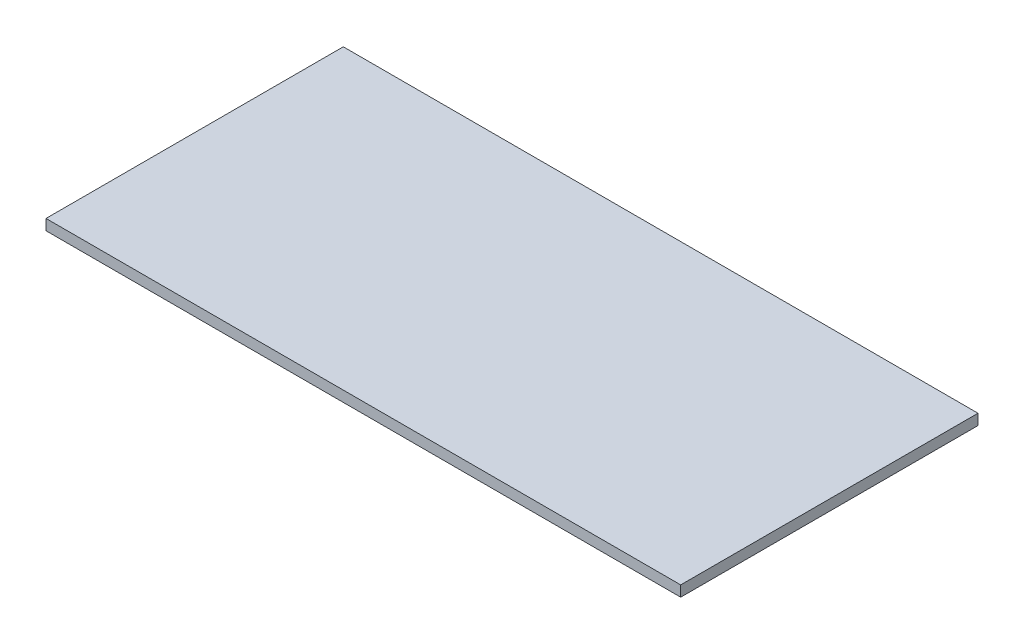
SolidWorks part; units mm, degrees
ref_plane "Front Plane" through (0, 0, 0) normal (0, 0, 1) x (1, 0, 0)
ref_plane "Top Plane" through (0, 0, 0) normal (0, 1, 0) x (1, 0, 0)
ref_plane "Right Plane" through (0, 0, 0) normal (1, 0, 0) x (0, 0, -1)
sketch "Sketch1" plane through (0, 0, 0) normal (0, 1, 0) x (1, 0, 0)
  line L1 (95, 44.5) -> (-95, 44.5)
  line L2 (95, 44.5) -> (95, -44.5)
  line L3 (95, -44.5) -> (-95, -44.5)
  line L4 (-95, 44.5) -> (-95, -44.5)
  line L5 (95, 44.5) -> (-95, -44.5) construction
  line L6 (95, -44.5) -> (-95, 44.5) construction
  point P0 (0, 0)
  dimension "D1" = 190
  dimension "D2" = 89
extrude "Boss-Extrude1" add sketch "Sketch1" along normal blind 3.2
